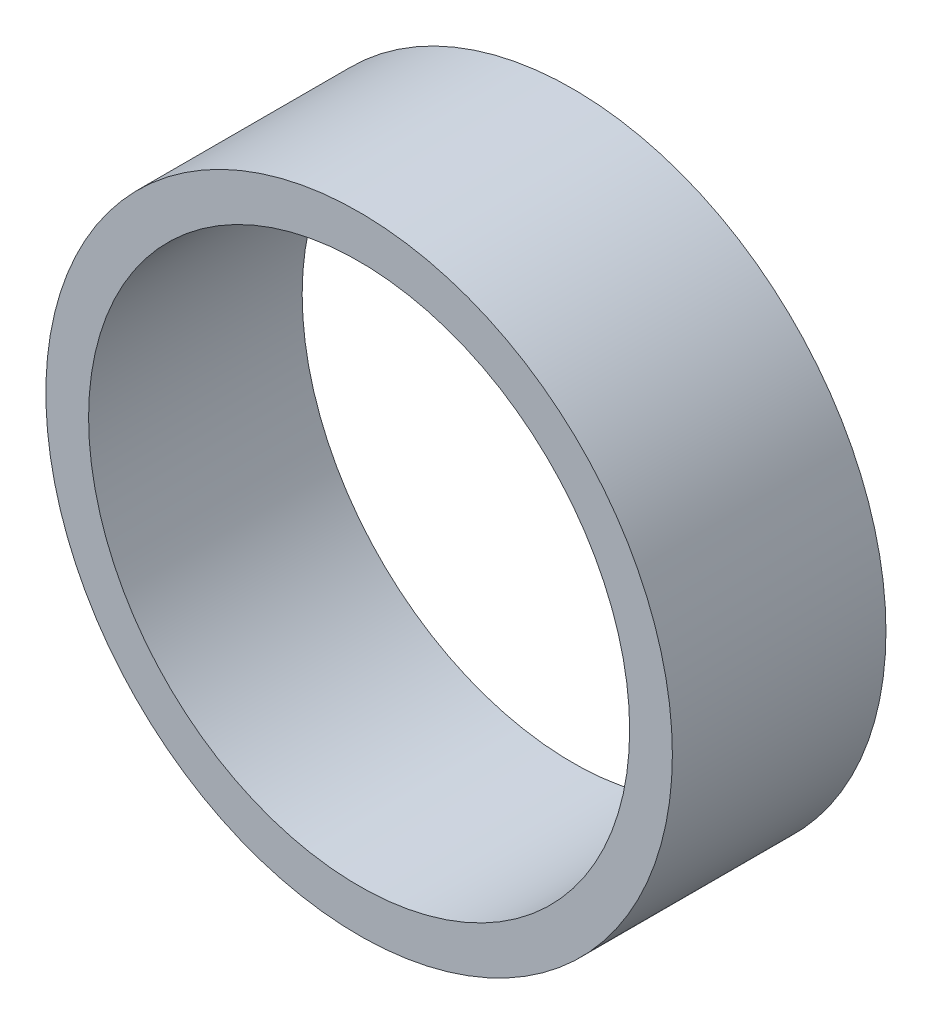
SolidWorks part; units mm, degrees
ref_plane "前视基准面" through (0, 0, 0) normal (0, 0, 1) x (1, 0, 0)
ref_plane "上视基准面" through (0, 0, 0) normal (0, 1, 0) x (1, 0, 0)
ref_plane "右视基准面" through (0, 0, 0) normal (1, 0, 0) x (0, 0, -1)
sketch "草图1" plane through (0, 0, 0) normal (0, 0, 1) x (1, 0, 0)
  circle A0 centre (0, 0) radius 19
  circle A1 centre (0, 0) radius 22
  dimension "D1" = 38
  dimension "D2" = 44
extrude "凸台-拉伸1" add sketch "草图1" along normal blind 15
